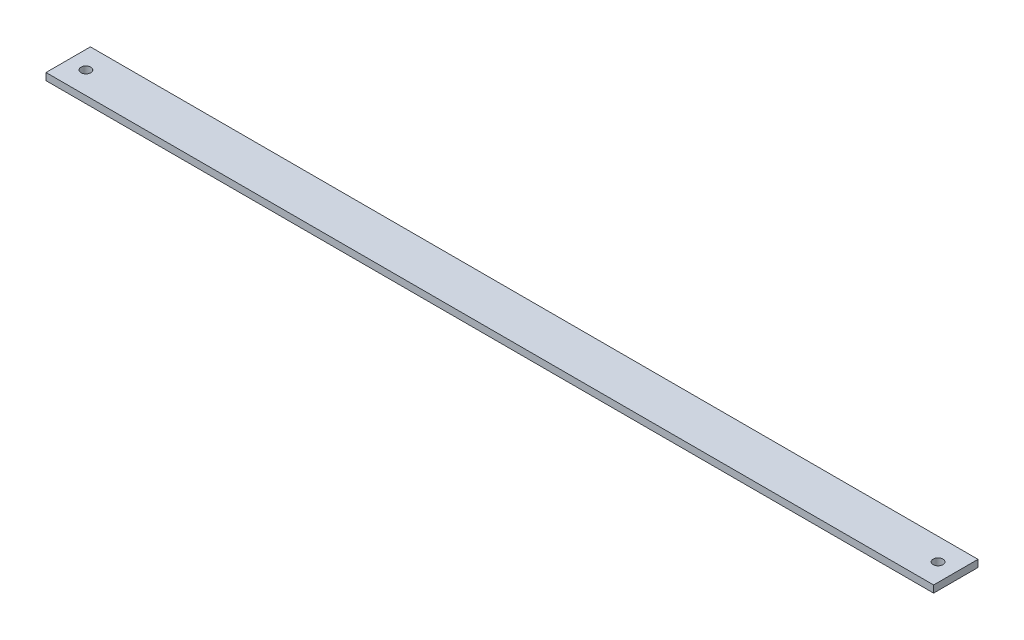
SolidWorks part; units mm, degrees
material "Plain Carbon Steel"
ref_plane "Front Plane" through (0, 0, 0) normal (0, 0, 1) x (1, 0, 0)
ref_plane "Top Plane" through (0, 0, 0) normal (0, 1, 0) x (1, 0, 0)
ref_plane "Right Plane" through (0, 0, 0) normal (1, 0, 0) x (0, 0, -1)
sketch "Sketch1" plane through (0, 0, 0) normal (1, 0, 0) x (0, 0, -1)
  line L1 (-12.5, 2) -> (12.5, 2)
  line L2 (-12.5, 2) -> (-12.5, -2)
  line L3 (-12.5, -2) -> (12.5, -2)
  line L4 (12.5, 2) -> (12.5, -2)
  line L5 (-12.5, 2) -> (12.5, -2) construction
  line L6 (-12.5, -2) -> (12.5, 2) construction
  point P0 (0, 0)
  dimension "D1" = 4
  dimension "D2" = 25
extrude "Boss-Extrude1" add sketch "Sketch1" along normal mid plane 500
sketch "Sketch2" plane through (0, 2, 0) normal (0, 1, 0) x (1, 0, 0)
  line L0 (0, 0) -> (0, 71.7345) construction
  circle A0 centre (-240, 0) radius 2.75
  circle A1 centre (240, 0) radius 2.75
  point P7 (0, 0)
  dimension "D1" = 5.5
  dimension "D2" = 480
extrude "Cut-Extrude1" cut sketch "Sketch2" against normal through all
